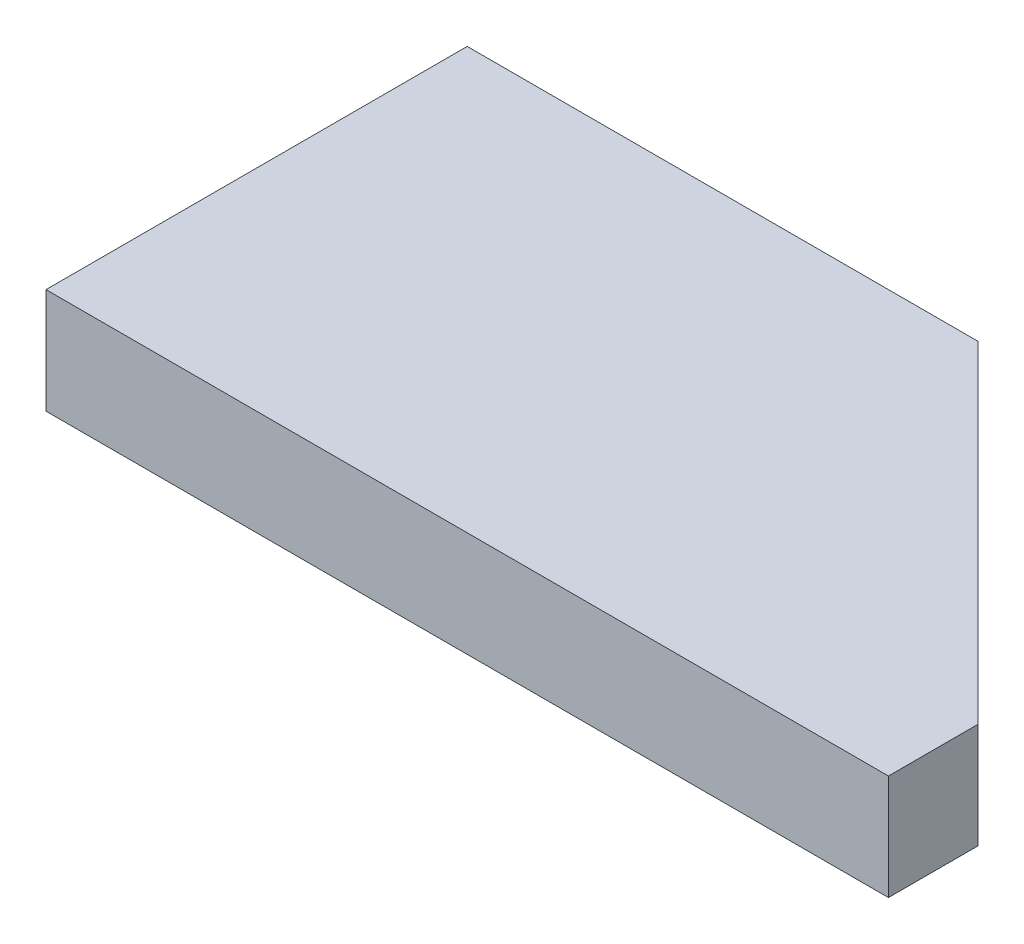
SolidWorks part; units mm, degrees
ref_plane "Front Plane" through (0, 0, 0) normal (0, 0, 1) x (1, 0, 0)
ref_plane "Top Plane" through (0, 0, 0) normal (0, 1, 0) x (1, 0, 0)
ref_plane "Right Plane" through (0, 0, 0) normal (1, 0, 0) x (0, 0, -1)
sketch "Sketch1" plane through (0, 0, 0) normal (0, 1, 0) x (1, 0, 0)
  line L1 (0, 0) -> (25.4, 0)
  line L2 (0, 0) -> (0, 12.7)
  line L3 (0, 12.7) -> (25.4, 12.7)
  line L4 (25.4, 0) -> (25.4, 12.7)
  dimension "D1" = 25.4
  dimension "D2" = 12.7
extrude "Boss-Extrude1" add sketch "Sketch1" along normal blind 3.175
chamfer "Chamfer1" distance 10 angle 45 1 edges at (25.4, 1.5875, -12.7)
